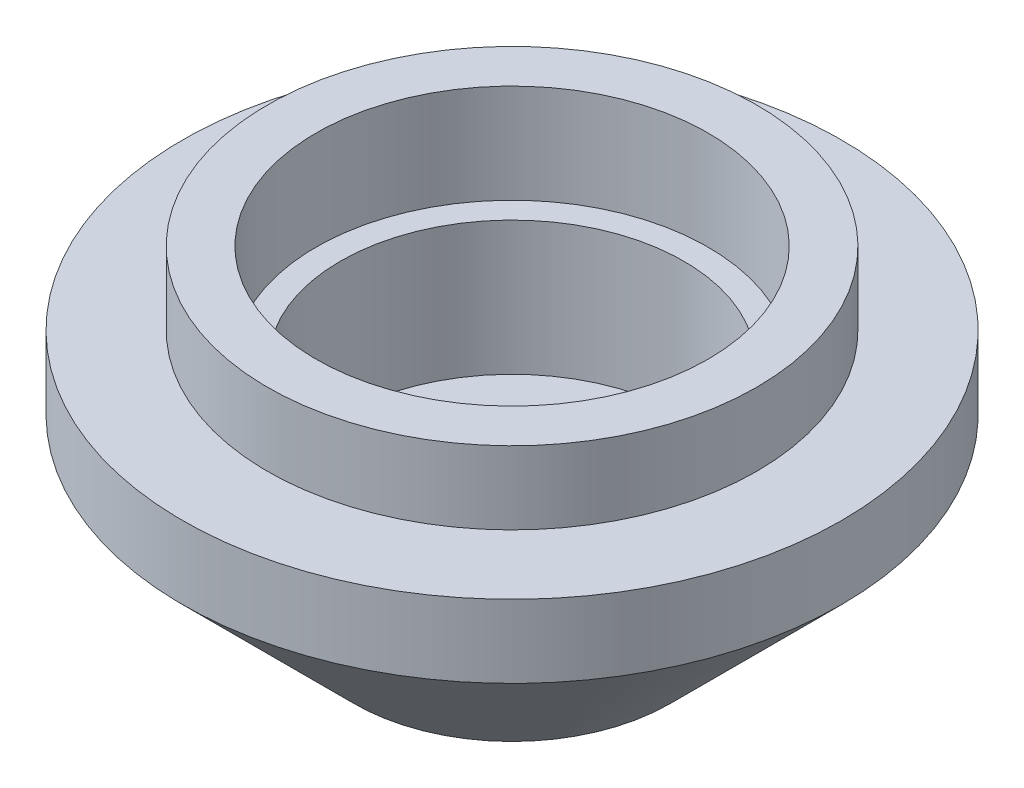
SolidWorks part; units mm, degrees
ref_plane "Front Plane" through (0, 0, 0) normal (0, 0, 1) x (1, 0, 0)
ref_plane "Top Plane" through (0, 0, 0) normal (0, 1, 0) x (1, 0, 0)
ref_plane "Right Plane" through (0, 0, 0) normal (1, 0, 0) x (0, 0, -1)
sketch "Sketch1" plane through (0, 0, 0) normal (0, 0, 1) x (1, 0, 0)
  line L0 (0, 0) -> (6.5, 0)
  line L1 (6.5, 0) -> (13.5711, 7.0711)
  line L2 (13.5711, 7.0711) -> (13.5711, 10.0711)
  line L3 (13.5711, 10.0711) -> (10.0711, 10.0711)
  line L4 (10.0711, 10.0711) -> (10.0711, 13.0711)
  line L5 (10.0711, 13.0711) -> (8.0711, 13.0711)
  line L6 (8.0711, 13.0711) -> (8.0711, 9)
  line L7 (8.0711, 9) -> (7.0711, 9)
  line L8 (7.0711, 9) -> (7.0711, 3.5)
  line L9 (7.0711, 3.5) -> (0, 3.5)
  line L10 (0, 3.5) -> (0, 0)
  line L11 (0, 0) -> (0, 17.9441) construction
  dimension "D1" = 6.5
  dimension "D2" = 10
  dimension "D3" = 135
  dimension "D4" = 3
  dimension "D5" = 3.5
  dimension "D6" = 3
  dimension "D7" = 2
  dimension "D8" = 1
  dimension "D9" = 5.5
  dimension "D10" = 3.5
revolve "Revolve1" add sketch "Sketch1" angle 360 about L11
